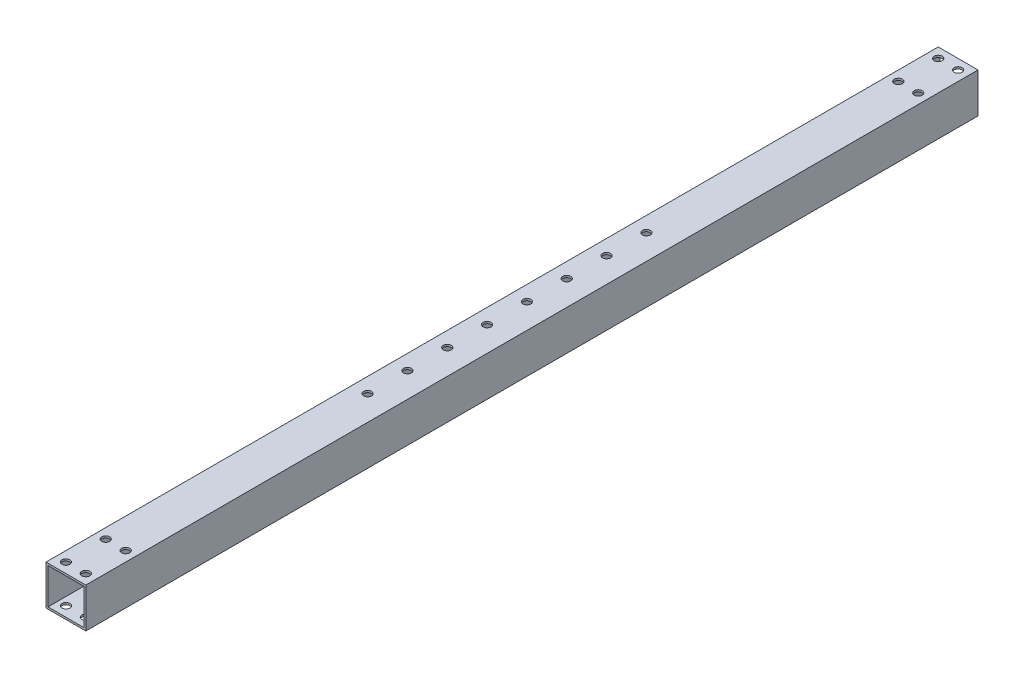
SolidWorks part; units mm, degrees
ref_plane "前视基准面" through (0, 0, 0) normal (0, 0, 1) x (1, 0, 0)
ref_plane "上视基准面" through (0, 0, 0) normal (0, 1, 0) x (1, 0, 0)
ref_plane "右视基准面" through (0, 0, 0) normal (1, 0, 0) x (0, 0, -1)
sketch "草图1" plane through (0, 0, 0) normal (0, 0, 1) x (1, 0, 0)
  line L1 (0, 0) -> (20, 0)
  line L2 (0, 0) -> (0, 20)
  line L3 (0, 20) -> (20, 20)
  line L4 (20, 0) -> (20, 20)
  dimension "D1" = 20
  dimension "D2" = 20
extrude "拉伸-薄壁1" add sketch "草图1" along normal blind 448 thin thin type one direction reverse wall 1
sketch "草图4" plane through (0, 20, 0) normal (0, 1, 0) x (1, 0, 0)
  line L0 (20, -224) -> (0, -224) construction
  line L1 (5, -423) -> (15, -423) construction
  line L2 (5, -423) -> (5, -443) construction
  line L3 (5, -443) -> (15, -443) construction
  line L4 (15, -423) -> (15, -443) construction
  line L5 (20, -448) -> (20, 0) construction
  line L6 (0, -448) -> (0, 0) construction
  line L7 (20, -448) -> (0, -448) construction
  line L8 (15, -25) -> (15, -5) construction
  line L9 (5, -5) -> (15, -5) construction
  line L10 (5, -25) -> (5, -5) construction
  line L11 (5, -25) -> (15, -25) construction
  line L12 (7.5, -154) -> (7.5, -294) construction
  circle A0 centre (5, -423) radius 2
  circle A1 centre (15, -423) radius 2
  circle A2 centre (15, -443) radius 2
  circle A3 centre (5, -443) radius 2
  circle A4 centre (5, -5) radius 2
  circle A5 centre (15, -5) radius 2
  circle A6 centre (15, -25) radius 2
  circle A7 centre (5, -25) radius 2
  circle A8 centre (7.5, -154) radius 2
  circle A9 centre (7.5, -174) radius 2
  circle A10 centre (7.5, -194) radius 2
  circle A11 centre (7.5, -214) radius 2
  circle A12 centre (7.5, -234) radius 2
  circle A13 centre (7.5, -254) radius 2
  circle A14 centre (7.5, -274) radius 2
  circle A15 centre (7.5, -294) radius 2
  point P35 (7.5, -224)
  dimension "D5" = 4
  dimension "D8" = 4
  dimension "D9" = 4
  dimension "D1" = 5
  dimension "D2" = 5
  dimension "D3" = 5
  dimension "D4" = 20
  dimension "D6" = 7.5
  dimension "D7" = 70
  dimension "D10" = 20
extrude "切除-拉伸1" cut sketch "草图4" against normal through all
